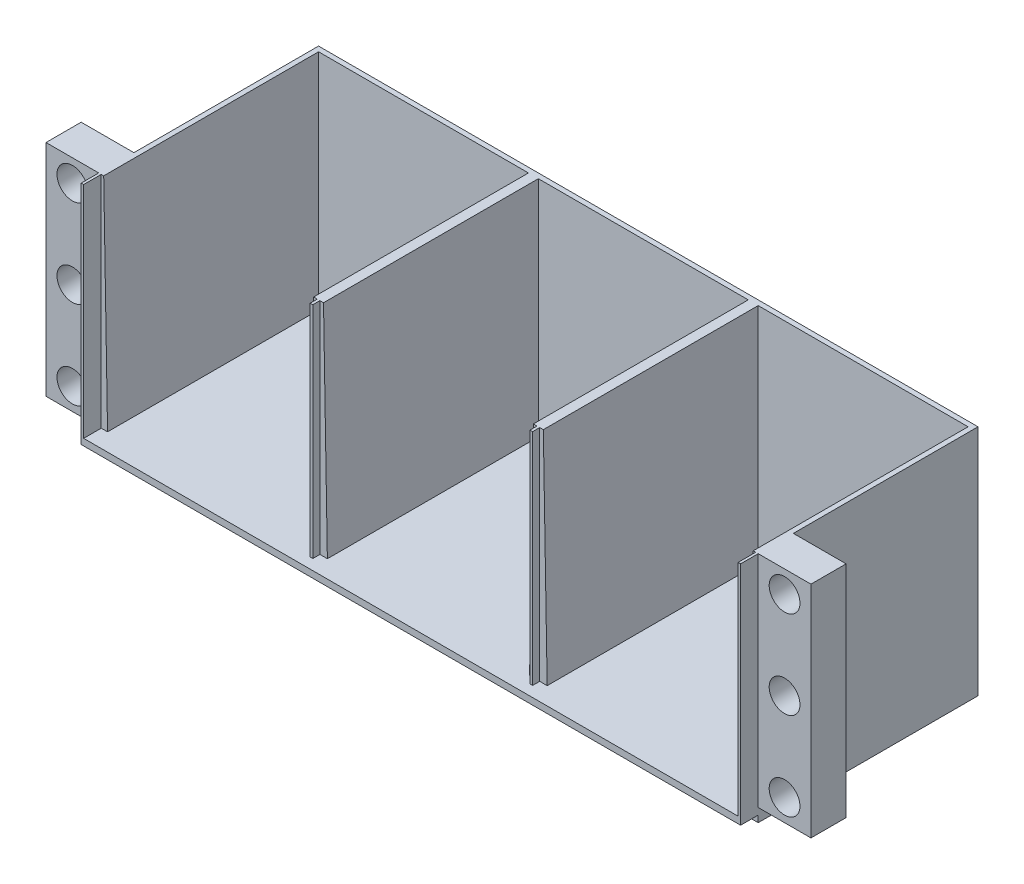
SolidWorks part; units mm, degrees
ref_plane "Front Plane" through (0, 0, 0) normal (0, 0, 1) x (1, 0, 0)
ref_plane "Top Plane" through (0, 0, 0) normal (0, 1, 0) x (1, 0, 0)
ref_plane "Right Plane" through (0, 0, 0) normal (1, 0, 0) x (0, 0, -1)
sketch "Sketch2" plane through (0, 0, 0) normal (0, 1, 0) x (1, 0, 0)
  line L0 (25, 25) -> (25, 0) construction
  line L5 (0, 0) -> (75, 0)
  line L6 (0, 0) -> (0, 25)
  line L7 (0, 25) -> (75, 25)
  line L9 (50, 25) -> (50, 0) construction
  line L10 (75, 25) -> (75, 0)
  dimension "D3" = 25
  dimension "D4" = 25
  dimension "D5" = 25
extrude "Boss-Extrude1" add sketch "Sketch2" along normal blind 1.5
sketch "Sketch4" plane through (0, 1.5, 0) normal (0, 1, 0) x (1, 0, 0)
  line L1 (24, 25) -> (26, 25)
  line L3 (0, 25) -> (75, 25) construction
  line L4 (24, 0) -> (26, 0)
  line L5 (0, 0) -> (75, 0) construction
  line L6 (49, 25) -> (51, 25)
  line L7 (49, 0) -> (51, 0)
  line L8 (24, 24) -> (24, 0)
  line L9 (26, 24) -> (26, 0)
  line L10 (49, 24) -> (49, 0)
  line L11 (51, 24) -> (51, 0)
  line L12 (24, 24) -> (1, 24)
  line L13 (1, 24) -> (1, 0)
  line L15 (0, 0) -> (0, 25) construction
  line L16 (24, 25) -> (0, 25)
  line L17 (0, 25) -> (0, 0)
  line L19 (26, 24) -> (49, 24)
  line L21 (26, 25) -> (49, 25)
  line L23 (51, 24) -> (74, 24)
  line L24 (74, 24) -> (74, 0)
  line L26 (75, 25) -> (75, 0) construction
  line L27 (51, 25) -> (75, 25)
  line L28 (75, 25) -> (75, 0)
  line L30 (1, 0) -> (0, 0)
  line L31 (74, 0) -> (75, 0)
  point P0 (25, 25)
  point P13 (25, 0)
  point P18 (50, 25)
  point P23 (50, 0)
  dimension "D1" = 2
  dimension "D2" = 2
  dimension "D3" = 2
  dimension "D4" = 2
  dimension "D5" = 1
  dimension "D6" = 1
  dimension "D8" = 1
extrude "Boss-Extrude5" add sketch "Sketch4" along normal blind 25 draft 1
sketch "Sketch6" plane through (0, 0, 0) normal (0, 0, 1) x (1, 0, 0)
  line L0 (75, 1.5) -> (75, 0) construction
  line L5 (0, 1.5) -> (75, 1.5)
  line L6 (0, 1.5) -> (0, 0.75)
  line L7 (0, 0.75) -> (75, 0.75)
  line L8 (75, 1.5) -> (75, 0.75)
extrude "Boss-Extrude6" add sketch "Sketch6" along normal blind 2
sketch "Sketch7" plane through (0, 0.4367, -25.0186) normal (0, 0.0175, -0.9998) x (-1, 0, 0)
  line L0 (-74.5636, 26.0673) -> (-75, 1.0635) construction
  line L1 (-75, -0.4363) -> (-74.9751, -0.4363)
  line L2 (-75, -0.4363) -> (-75, 2.4929)
  line L3 (-75, 2.4929) -> (-74.9751, 2.4929)
  line L4 (-74.9751, -0.4363) -> (-74.9751, 2.4929)
sketch "Sketch8" plane through (0, 26.5, 0) normal (0, 1, 0) x (1, 0, 0)
  line L0 (0, 25) -> (0, 0) construction
  line L1 (0, 0) -> (0.4364, 0.4364) construction
  line L2 (0.4364, 0.4364) -> (0.4364, 24.5636) construction
  line L3 (75, 0) -> (75, 25) construction
  line L4 (74.5636, 24.5636) -> (74.5636, 0.4364) construction
  line L5 (74.5636, 0.4364) -> (75, 0) construction
  line L6 (75, 25) -> (0, 25) construction
  line L7 (0.4364, 24.5636) -> (74.5636, 24.5636) construction
  line L8 (0, 25) -> (0, 0)
  line L9 (0, 0) -> (0.4364, 0.4364)
  line L10 (0.4364, 0.4364) -> (0.4364, 24.5636)
  line L11 (75, 0) -> (75, 25)
  line L12 (74.5636, 24.5636) -> (74.5636, 0.4364)
  line L13 (74.5636, 0.4364) -> (75, 0)
  line L14 (75, 25) -> (0, 25)
  line L15 (0.4364, 24.5636) -> (74.5636, 24.5636)
extrude "Boss-Extrude7" add sketch "Sketch8" against normal up to surface (25 mm away) up to face at (37.5, 1.5, -8.75)
ref_plane "Plane1" through (0, 0, 0) normal (0, 0, -1) x (-1, 0, 0)
sketch "Sketch9" plane through (0, 0, 0) normal (0, 0, -1) x (-1, 0, 0)
  line L0 (-75, 1.5) -> (-75, 26.5) construction
  line L1 (-75, 26.5) -> (-74.5636, 26.5) construction
  line L2 (-74, 1.5) -> (-75, 1.5) construction
  line L3 (-74.5636, 26.5) -> (-74.4364, 26.5) construction
  line L4 (-74.4364, 26.5) -> (-74, 1.5) construction
  line L5 (-49, 1.5) -> (-51, 1.5) construction
  line L6 (-51, 1.5) -> (-50.5636, 26.5) construction
  line L7 (-50.5636, 26.5) -> (-49.4364, 26.5) construction
  line L8 (-49.4364, 26.5) -> (-49, 1.5) construction
  line L9 (-0.4364, 26.5) -> (0, 26.5) construction
  line L10 (0, 26.5) -> (0, 1.5) construction
  line L11 (-24, 1.5) -> (-26, 1.5) construction
  line L12 (-26, 1.5) -> (-25.5636, 26.5) construction
  line L13 (-25.5636, 26.5) -> (-24.4364, 26.5) construction
  line L14 (-24.4364, 26.5) -> (-24, 1.5) construction
  line L15 (0, 1.5) -> (-1, 1.5) construction
  line L16 (-1, 1.5) -> (-0.5636, 26.5) construction
  line L17 (-0.5636, 26.5) -> (-0.4364, 26.5) construction
  line L18 (-75, 1.5) -> (-75, 26.5)
  line L19 (-75, 26.5) -> (-74.5636, 26.5)
  line L20 (-74, 1.5) -> (-75, 1.5)
  line L21 (-74.5636, 26.5) -> (-74.4364, 26.5)
  line L22 (-74.4364, 26.5) -> (-74, 1.5)
  line L23 (-49, 1.5) -> (-51, 1.5)
  line L24 (-51, 1.5) -> (-50.5636, 26.5)
  line L25 (-50.5636, 26.5) -> (-49.4364, 26.5)
  line L26 (-49.4364, 26.5) -> (-49, 1.5)
  line L27 (-0.4364, 26.5) -> (0, 26.5)
  line L28 (0, 26.5) -> (0, 1.5)
  line L29 (-24, 1.5) -> (-26, 1.5)
  line L30 (-26, 1.5) -> (-25.5636, 26.5)
  line L31 (-25.5636, 26.5) -> (-24.4364, 26.5)
  line L32 (-24.4364, 26.5) -> (-24, 1.5)
  line L33 (0, 1.5) -> (-1, 1.5)
  line L34 (-1, 1.5) -> (-0.5636, 26.5)
  line L35 (-0.5636, 26.5) -> (-0.4364, 26.5)
extrude "Boss-Extrude8" add sketch "Sketch9" along normal up to surface (0.4364 mm away) contours L18 L19 L21 L22 L20 | L23 L24 L25 L26 | L29 L30 L31 L32 | L27 L28 L33 L34 L35
sketch "Sketch10" plane through (0, 0, 0) normal (0, 0, 1) x (1, 0, 0)
  line L0 (0.2818, 26.5) -> (0.2818, 1.5) construction
  line L1 (0.5636, 26.5) -> (0, 26.5) construction
  line L2 (0, 1.5) -> (1, 1.5) construction
  line L3 (74.7182, 26.5) -> (74.7182, 1.5) construction
  line L4 (0.2818, 26.5) -> (0, 26.5)
  line L5 (0.2818, 26.5) -> (0.2818, 1.5)
  line L6 (0.2818, 1.5) -> (0, 1.5)
  line L7 (0, 26.5) -> (0, 1.5)
  line L8 (75, 26.5) -> (74.4364, 26.5) construction
  line L9 (74, 1.5) -> (75, 1.5) construction
  line L11 (75, 26.5) -> (74.7182, 26.5)
  line L12 (75, 26.5) -> (75, 1.5)
  line L13 (75, 1.5) -> (74.7182, 1.5)
  line L14 (74.7182, 26.5) -> (74.7182, 1.5)
extrude "Boss-Extrude9" add sketch "Sketch10" along normal blind 2
sketch "Sketch12" plane through (75, 0, 0) normal (1, 0, 0) x (0, 0, -1)
  line L0 (0, 0) -> (0, 26.5) construction
sketch "Sketch13" plane through (0, 0, 0) normal (-1, 0, 0) x (0, 0, 1)
  line L1 (0, 26.5) -> (-4, 26.5)
  line L2 (0, 26.5) -> (0, 1.5)
  line L3 (0, 1.5) -> (-4, 1.5)
  line L4 (-4, 26.5) -> (-4, 1.5)
  dimension "D1" = 25
  dimension "D2" = 4
extrude "Boss-Extrude10" add sketch "Sketch13" along normal blind 6
sketch "Sketch14" plane through (75, 0, 0) normal (1, 0, 0) x (0, 0, -1)
  line L1 (0, 26.5) -> (4, 26.5)
  line L2 (0, 26.5) -> (0, 1.5)
  line L3 (0, 1.5) -> (4, 1.5)
  line L4 (4, 26.5) -> (4, 1.5)
  dimension "D1" = 25
  dimension "D2" = 4
extrude "Boss-Extrude11" add sketch "Sketch14" along normal blind 6
sketch "Sketch15" plane through (0, 0, 0) normal (0, 0, 1) x (1, 0, 0)
  line L0 (-3, 26.5) -> (-3, 1.5) construction
  line L1 (-6, 26.5) -> (0, 26.5) construction
  line L2 (-6, 1.5) -> (0, 1.5) construction
  line L3 (78, 26.5) -> (78, 1.5) construction
  line L4 (81, 26.5) -> (75, 26.5) construction
  line L5 (81, 1.5) -> (75, 1.5) construction
  circle A0 centre (-3, 24) radius 1.75
  circle A1 centre (78, 24) radius 1.75
  circle A2 centre (-3, 14) radius 1.75
  circle A3 centre (-3, 4) radius 1.75
  circle A4 centre (78, 14) radius 1.75
  circle A5 centre (78, 4) radius 1.75
  dimension "D1" = 3.5
  dimension "D2" = 3.5
  dimension "D3" = 2.5
  dimension "D5" = 2.5
  dimension "D4" = 3
  dimension "D6" = 3
extrude "Cut-Extrude1" cut sketch "Sketch15" against normal blind 6
sketch "Sketch16" plane through (0, 0, 0) normal (0, 0, 1) x (1, 0, 0)
  line L0 (25, 26.5) -> (25, 1.5) construction
  line L1 (25.5636, 26.5) -> (24.4364, 26.5) construction
  line L2 (24, 1.5) -> (26, 1.5) construction
  line L3 (50, 26.5) -> (50, 1.5) construction
  line L4 (50.5636, 26.5) -> (49.4364, 26.5) construction
  line L5 (49, 1.5) -> (51, 1.5) construction
  line L6 (25, 14) -> (50, 14) construction
  line L7 (74.7182, 1.5) -> (0.2818, 1.5) construction
  line L12 (24.85, 26.5) -> (25.15, 26.5)
  line L13 (24.85, 26.5) -> (24.85, 1.5)
  line L14 (24.85, 1.5) -> (25.15, 1.5)
  line L15 (25.15, 26.5) -> (25.15, 1.5)
  line L16 (24.85, 26.5) -> (25.15, 1.5) construction
  line L17 (24.85, 1.5) -> (25.15, 26.5) construction
  line L19 (49.85, 26.5) -> (50.15, 26.5)
  line L20 (49.85, 26.5) -> (49.85, 1.5)
  line L21 (49.85, 1.5) -> (50.15, 1.5)
  line L22 (50.15, 26.5) -> (50.15, 1.5)
  line L23 (49.85, 26.5) -> (50.15, 1.5) construction
  line L24 (49.85, 1.5) -> (50.15, 26.5) construction
  dimension "D1" = 0.3
  dimension "D2" = 0.3
extrude "Boss-Extrude12" add sketch "Sketch16" along normal blind 0.8
